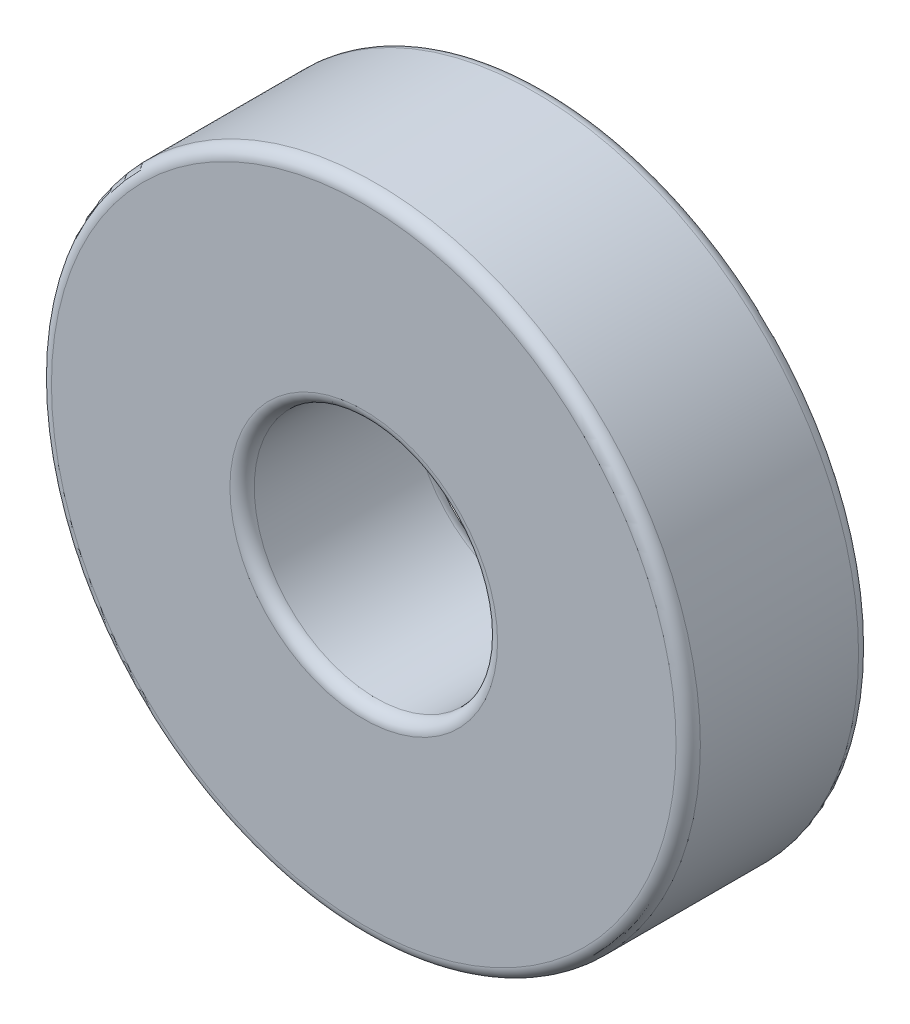
SolidWorks part; units mm, degrees
ref_plane "Alzado" through (0, 0, 0) normal (0, 0, 1) x (1, 0, 0)
ref_plane "Planta" through (0, 0, 0) normal (0, 1, 0) x (1, 0, 0)
ref_plane "Vista lateral" through (0, 0, 0) normal (1, 0, 0) x (0, 0, -1)
sketch "Croquis1" plane through (0, 0, 0) normal (0, 0, 1) x (1, 0, 0)
  circle A0 centre (0, 0) radius 6
  circle A1 centre (0, 0) radius 16
  dimension "D1" = 32
  dimension "D2" = 12
extrude "Saliente-Extruir1" add sketch "Croquis1" along normal blind 9
fillet "Redondeo1" radius 0.6 4 edges at (6, 0, 0) (6, 0, 9) (16, 0, 0) (16, 0, 9)
